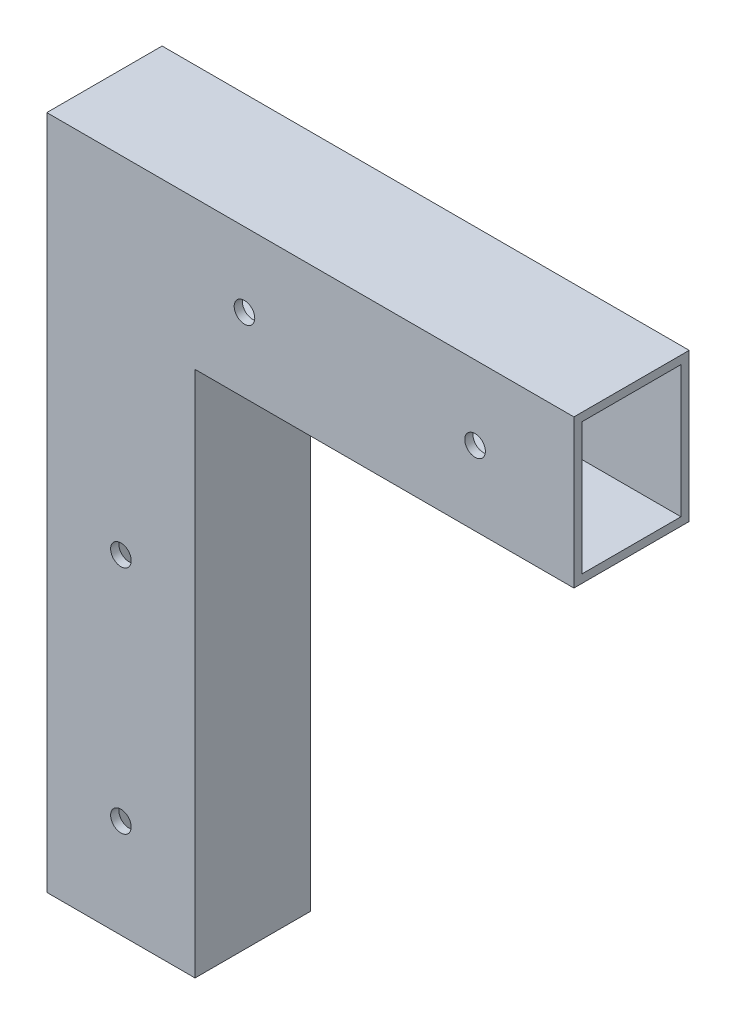
SolidWorks part; units mm, degrees
material "AISI 1020 Steel, Cold Rolled"
ref_plane "Front Plane" through (0, 0, 0) normal (0, 0, 1) x (1, 0, 0)
ref_plane "Top Plane" through (0, 0, 0) normal (0, 1, 0) x (1, 0, 0)
ref_plane "Right Plane" through (0, 0, 0) normal (1, 0, 0) x (0, 0, -1)
sketch "Sketch1" plane through (0, 0, 0) normal (0, 0, 1) x (1, 0, 0)
  line L1 (-57.15, -203.2) -> (57.15, -203.2)
  line L2 (-57.15, -203.2) -> (-57.15, 203.2)
  line L3 (-57.15, 203.2) -> (57.15, 203.2)
  line L4 (57.15, -203.2) -> (57.15, 203.2)
  line L5 (-57.15, -203.2) -> (57.15, 203.2) construction
  line L6 (-57.15, 203.2) -> (57.15, -203.2) construction
  point P0 (0, 0)
  dimension "D1" = 114.3
  dimension "D2" = 406.4
extrude "Boss-Extrude1" add sketch "Sketch1" along normal blind 88.9
sketch "Sketch2" plane through (0, 203.2, 0) normal (0, 1, 0) x (1, 0, 0)
  line L0 (-57.15, 0) -> (349.25, 0)
  line L1 (-57.15, -88.9) -> (-57.15, 0) construction
  line L2 (349.25, 0) -> (349.25, -88.9)
  line L3 (349.25, -88.9) -> (-57.15, -88.9)
  line L4 (-57.15, -88.9) -> (-57.15, 0)
  line L6 (57.15, 0) -> (-57.15, 0) construction
  dimension "D1" = 406.4
  dimension "D2" = 88.9
  dimension "D3" = 0
extrude "Boss-Extrude2" add sketch "Sketch2" along normal blind 114.3
sketch "Sketch3" plane through (349.25, 0, 0) normal (1, 0, 0) x (0, 0, -1)
  line L0 (-88.9, 317.5) -> (0, 317.5) construction
  line L1 (-82.55, 209.55) -> (-6.35, 209.55)
  line L2 (-82.55, 209.55) -> (-82.55, 311.15)
  line L3 (-82.55, 311.15) -> (-6.35, 311.15)
  line L4 (-6.35, 209.55) -> (-6.35, 311.15)
  line L5 (-82.55, 209.55) -> (-6.35, 311.15) construction
  line L6 (-82.55, 311.15) -> (-6.35, 209.55) construction
  line L7 (-88.9, 317.5) -> (-88.9, 203.2) construction
  point P0 (-44.45, 260.35)
  dimension "D1" = 76.2
  dimension "D2" = 101.6
  dimension "D3" = 6.35
  dimension "D4" = 6.35
extrude "Cut-Extrude1" cut sketch "Sketch3" against normal blind 400.05
sketch "Sketch4" plane through (0, -203.2, 0) normal (0, -1, 0) x (1, 0, 0)
  line L0 (-57.15, 88.9) -> (-57.15, 0) construction
  line L1 (-50.8, 82.55) -> (50.8, 82.55)
  line L2 (-50.8, 82.55) -> (-50.8, 6.35)
  line L3 (-50.8, 6.35) -> (50.8, 6.35)
  line L4 (50.8, 82.55) -> (50.8, 6.35)
  line L5 (-50.8, 82.55) -> (50.8, 6.35) construction
  line L6 (-50.8, 6.35) -> (50.8, 82.55) construction
  line L7 (-57.15, 88.9) -> (57.15, 88.9) construction
  point P0 (0, 44.45)
  dimension "D1" = 101.6
  dimension "D2" = 76.2
  dimension "D3" = 6.35
  dimension "D4" = 6.35
extrude "Cut-Extrude3" cut sketch "Sketch4" against normal blind 400.05
sketch "Sketch5" plane through (0, 0, 88.9) normal (0, 0, 1) x (1, 0, 0)
  line L0 (349.25, 317.5) -> (349.25, 203.2) construction
  line L1 (-57.15, 317.5) -> (349.25, 317.5) construction
  circle A0 centre (273.05, 260.35) radius 7.9375
  circle A1 centre (95.25, 260.35) radius 7.9375
  dimension "D1" = 15.875
  dimension "D2" = 15.875
  dimension "D3" = 177.8
  dimension "D4" = 76.2
  dimension "D5" = 57.15
extrude "Cut-Extrude4" cut sketch "Sketch5" against normal blind 400.05
sketch "Sketch6" plane through (0, 0, 88.9) normal (0, 0, 1) x (1, 0, 0)
  line L0 (-57.15, -203.2) -> (57.15, -203.2) construction
  circle A0 centre (0, -127) radius 7.9375
  circle A1 centre (0, 50.8) radius 7.9375
  dimension "D1" = 15.875
  dimension "D2" = 15.875
  dimension "D3" = 177.8
  dimension "D4" = 76.2
extrude "Cut-Extrude5" cut sketch "Sketch6" against normal blind 400.05
